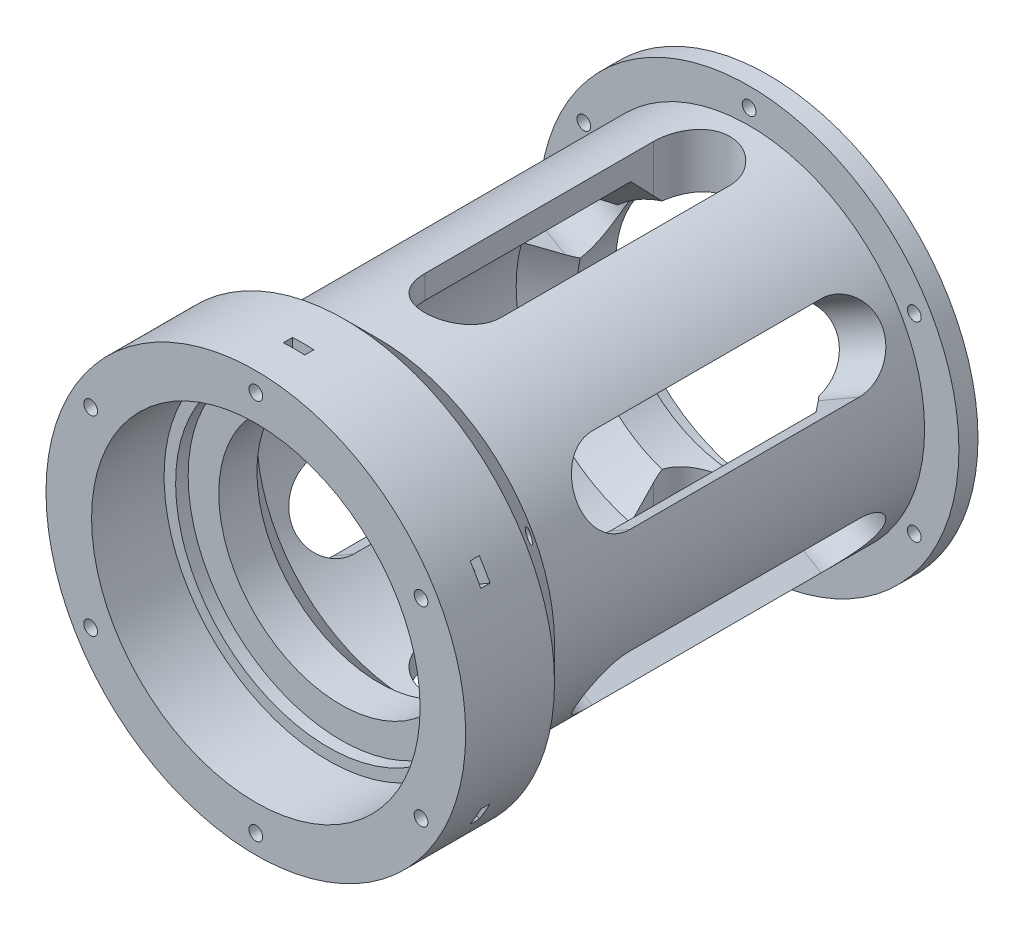
SolidWorks part; units mm, degrees
ref_plane "Front Plane" through (0, 0, 0) normal (0, 0, 1) x (1, 0, 0)
ref_plane "Top Plane" through (0, 0, 0) normal (0, 1, 0) x (1, 0, 0)
ref_plane "Right Plane" through (0, 0, 0) normal (1, 0, 0) x (0, 0, -1)
sketch "Sketch2" plane through (0, 0, 0) normal (0, 1, 0) x (1, 0, 0)
  line L0 (0, -164.1175) -> (0, 109.4658) construction
  line L1 (-106.4732, 0) -> (104.2682, 0) construction
  line L2 (55, 0) -> (40.025, 0)
  line L3 (40.025, 0) -> (40.025, -8)
  line L7 (40.025, -112) -> (40.025, -115.28)
  line L8 (40.025, -115.28) -> (43.05, -115.28)
  line L9 (43.05, -115.28) -> (43.05, -134.28)
  line L10 (43.05, -134.28) -> (55, -134.28)
  line L11 (55, -134.28) -> (55, -111)
  line L13 (46, -102) -> (46, -5)
  line L14 (46, -5) -> (55, -5)
  line L15 (55, -5) -> (55, 0)
  line L16 (40.025, -112) -> (32, -112)
  line L17 (32, -112) -> (32, -102)
  line L18 (32, -8) -> (40.025, -8)
  line L19 (55, -111) -> (46, -102)
  line L20 (32, -102) -> (40.025, -93.975)
  line L21 (40.025, -93.975) -> (40.025, -26.025)
  line L22 (40.025, -26.025) -> (32, -18)
  line L23 (32, -18) -> (32, -8)
  dimension "D2" = 64
  dimension "D3" = 40.025
  dimension "D4" = 8
  dimension "D5" = 3.28
  dimension "D6" = 55
  dimension "D7" = 19
  dimension "D8" = 43.05
  dimension "D9" = 9
  dimension "D10" = 40.025
  dimension "D11" = 5
  dimension "D12" = 104
  dimension "D13" = 55
  dimension "D14" = 10
  dimension "D15" = 45
  dimension "D16" = 10
  dimension "D17" = 135
  dimension "D18" = 135
revolve "Revolve1" add sketch "Sketch2" angle 360 about L0
sketch "Sketch3" plane through (0, 0, 134.28) normal (0, 0, 1) x (1, 0, 0)
  line L0 (0, 57.5768) -> (0, -57.0977) construction
  circle A0 centre (0, 50) radius 1.8
  circle A1 centre (43.3013, 25) radius 1.8
  circle A2 centre (43.3013, -25) radius 1.8
  circle A3 centre (0, -50) radius 1.8
  circle A4 centre (-43.3013, -25) radius 1.8
  circle A5 centre (-43.3013, 25) radius 1.8
  point P17 (0, 0)
  dimension "D1" = 3.6
  dimension "D2" = 50
  dimension "D3" = 6
extrude "Cut-Extrude1" cut sketch "Sketch3" against normal through all
sketch "Sketch4" plane through (0, 0, 115.28) normal (0, 0, 1) x (1, 0, 0)
  line L0 (0, 59.4934) -> (0, -58.3754) construction
  line L1 (-2.45, 44.9333) -> (-2.45, 39.9499)
  line L2 (2.45, 44.9333) -> (2.45, 39.9499)
  circle A0 centre (0, 0) radius 40.025 construction
  circle A1 centre (0, 0) radius 43.05
  arc A3 (2.45, 39.9499) -> (-2.45, 39.9499) centre (0, 0) ccw
  circle A6 centre (0, 0) radius 43.05
  circle M5 centre (0, 0) radius 43.05
  circle M6 centre (0, 0) radius 40.025
  dimension "D2" = 2.45
  dimension "D1" = 0
extrude "Boss-Extrude1" add sketch "Sketch4" along normal blind 5 contours L0 A6 L1 M6 | L0 A3 L2 M5
ref_plane "Plane1" through (0, 0, 124.28) normal (0, 0, 1) x (1, 0, 0)
sketch "Sketch5" plane through (0, 0, 124.28) normal (0, 0, 1) x (1, 0, 0)
  line L0 (0, 71.302) -> (0, -65.8547) construction
  line L1 (-25.8624, 50) -> (32.4005, 50) construction
  line L2 (-2.8, 58.331) -> (-2.8, 47.2)
  line L3 (-2.8, 47.2) -> (2.8, 47.2)
  line L4 (2.8, 47.2) -> (2.8, 58.331)
  line L5 (2.8, 58.331) -> (-2.8, 58.331)
  line L6 (51.9161, 26.7406) -> (49.1161, 31.5904)
  line L7 (49.1161, 31.5904) -> (39.4764, 26.0249)
  line L8 (39.4764, 26.0249) -> (42.2764, 21.1751)
  line L9 (42.2764, 21.1751) -> (51.9161, 26.7406)
  line L10 (49.1161, -31.5904) -> (51.9161, -26.7406)
  line L11 (51.9161, -26.7406) -> (42.2764, -21.1751)
  line L12 (42.2764, -21.1751) -> (39.4764, -26.0249)
  line L13 (39.4764, -26.0249) -> (49.1161, -31.5904)
  line L14 (-2.8, -58.331) -> (2.8, -58.331)
  line L15 (2.8, -58.331) -> (2.8, -47.2)
  line L16 (2.8, -47.2) -> (-2.8, -47.2)
  line L17 (-2.8, -47.2) -> (-2.8, -58.331)
  line L18 (-51.9161, -26.7406) -> (-49.1161, -31.5904)
  line L19 (-49.1161, -31.5904) -> (-39.4764, -26.0249)
  line L20 (-39.4764, -26.0249) -> (-42.2764, -21.1751)
  line L21 (-42.2764, -21.1751) -> (-51.9161, -26.7406)
  line L22 (-49.1161, 31.5904) -> (-51.9161, 26.7406)
  line L23 (-51.9161, 26.7406) -> (-42.2764, 21.1751)
  line L24 (-42.2764, 21.1751) -> (-39.4764, 26.0249)
  line L25 (-39.4764, 26.0249) -> (-49.1161, 31.5904)
  point P33 (0, 0)
  dimension "D1" = 2.8
  dimension "D2" = 5.6
  dimension "D3" = 2.8
  dimension "D4" = 6
extrude "Cut-Extrude2" cut sketch "Sketch5" against normal blind 2.4
sketch "Sketch6" plane through (0, 0, 0) normal (0, 1, 0) x (1, 0, 0)
  line L0 (0, 38.0695) -> (0, -150.3703) construction
  line L1 (-10, -20) -> (-10, -80)
  line L2 (10, -20) -> (10, -80)
  arc A0 (10, -20) -> (-10, -20) centre (0, -20) ccw
  arc A1 (-10, -80) -> (10, -80) centre (0, -80) ccw
  dimension "D1" = 20
  dimension "D3" = 20
  dimension "D4" = 60
  dimension "D2" = 20
extrude "Cut-Extrude3" cut sketch "Sketch6" against normal through all both and the other way through all
pattern_circular "CirPattern1" count 3 over 360 about axis through (0, 0, 0) along (0, 0, 1) of "Cut-Extrude3"
